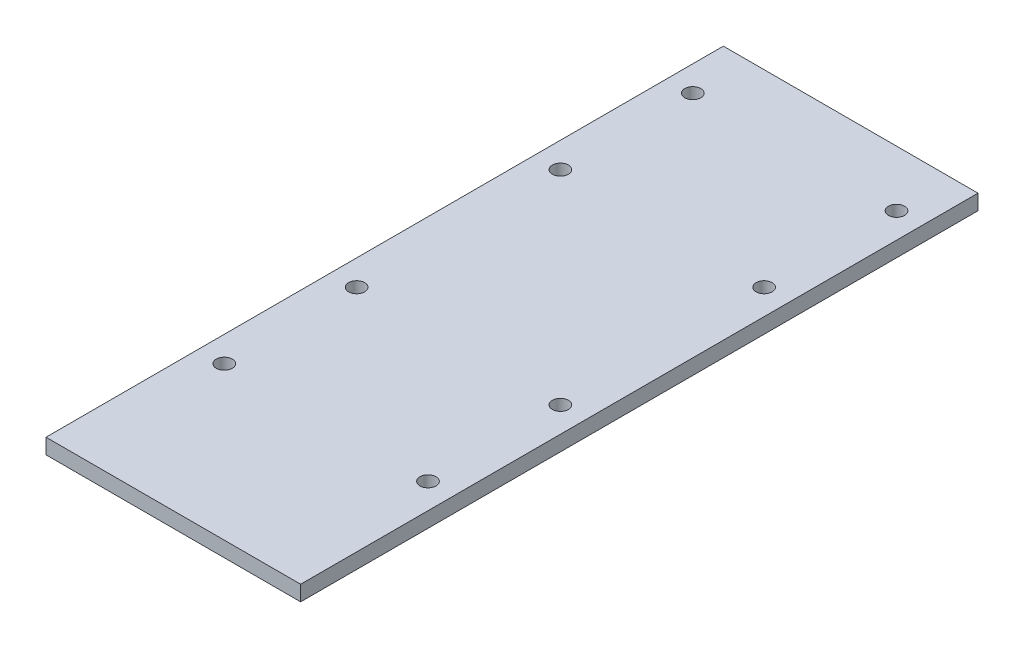
SolidWorks part; units mm, degrees
material "Thornel Mat VMA"
ref_plane "前视基准面" through (0, 0, 0) normal (0, 0, 1) x (1, 0, 0)
ref_plane "上视基准面" through (0, 0, 0) normal (0, 1, 0) x (1, 0, 0)
ref_plane "右视基准面" through (0, 0, 0) normal (1, 0, 0) x (0, 0, -1)
other "Configuration Table"
sketch "草图1" plane through (0, 0, 0) normal (0, 1, 0) x (1, 0, 0)
  line L1 (-25, 66.5) -> (25, 66.5)
  line L2 (-25, 66.5) -> (-25, -66.5)
  line L3 (-25, -66.5) -> (25, -66.5)
  line L4 (25, 66.5) -> (25, -66.5)
  line L5 (-25, 66.5) -> (25, -66.5) construction
  line L6 (-25, -66.5) -> (25, 66.5) construction
  line L7 (-20, 55.5) -> (20, 55.5) construction
  line L8 (-20, 55.5) -> (-20, 29.5) construction
  line L9 (-20, 29.5) -> (20, 29.5) construction
  line L10 (20, 55.5) -> (20, 29.5) construction
  line L11 (-20, 55.5) -> (20, 29.5) construction
  line L12 (-20, 29.5) -> (20, 55.5) construction
  line L13 (-20, -10.5) -> (20, -10.5) construction
  line L14 (-20, -10.5) -> (-20, -36.5) construction
  line L15 (-20, -36.5) -> (20, -36.5) construction
  line L16 (20, -10.5) -> (20, -36.5) construction
  line L17 (-20, -10.5) -> (20, -36.5) construction
  line L18 (-20, -36.5) -> (20, -10.5) construction
  circle A0 centre (-20, -36.5) radius 1.575
  circle A1 centre (-20, -10.5) radius 1.575
  circle A2 centre (20, -36.5) radius 1.575
  circle A3 centre (20, -10.5) radius 1.575
  circle A4 centre (20, 29.5) radius 1.575
  circle A5 centre (-20, 29.5) radius 1.575
  circle A6 centre (-20, 55.5) radius 1.575
  circle A7 centre (20, 55.5) radius 1.575
  point P0 (0, 0)
  point P6 (0, 42.5)
  point P11 (0, -23.5)
  dimension "D7" = 3.15
  dimension "D1" = 26
  dimension "D2" = 40
  dimension "D3" = 40
  dimension "D4" = 50
  dimension "D5" = 133
  dimension "D6" = 30
extrude "凸台-拉伸1" add sketch "草图1" along normal blind 3
